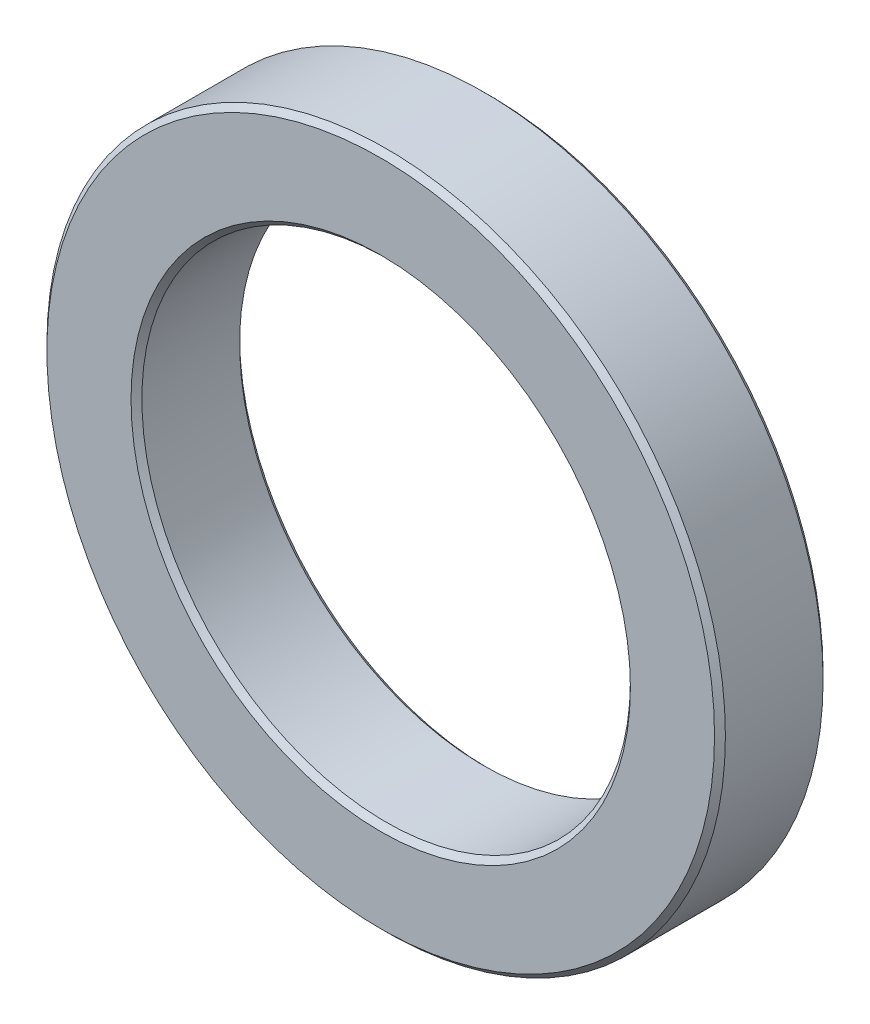
SolidWorks part; units mm, degrees
ref_plane "前视基准面" through (0, 0, 0) normal (0, 0, 1) x (1, 0, 0)
ref_plane "上视基准面" through (0, 0, 0) normal (0, 1, 0) x (1, 0, 0)
ref_plane "右视基准面" through (0, 0, 0) normal (1, 0, 0) x (0, 0, -1)
other "Configuration Table"
sketch "草图1" plane through (0, 0, 0) normal (0, 0, 1) x (1, 0, 0)
  circle A0 centre (0, 0) radius 62.5
  circle A1 centre (0, 0) radius 45
  dimension "D1" = 125
  dimension "D2" = 90
extrude "凸台-拉伸1" add sketch "草图1" along normal mid plane 20
chamfer "倒角1" distance 1 angle 45 4 edges at (62.5, 0, -10) (62.5, 0, 10) (45, 0, -10) (45, 0, 10)
